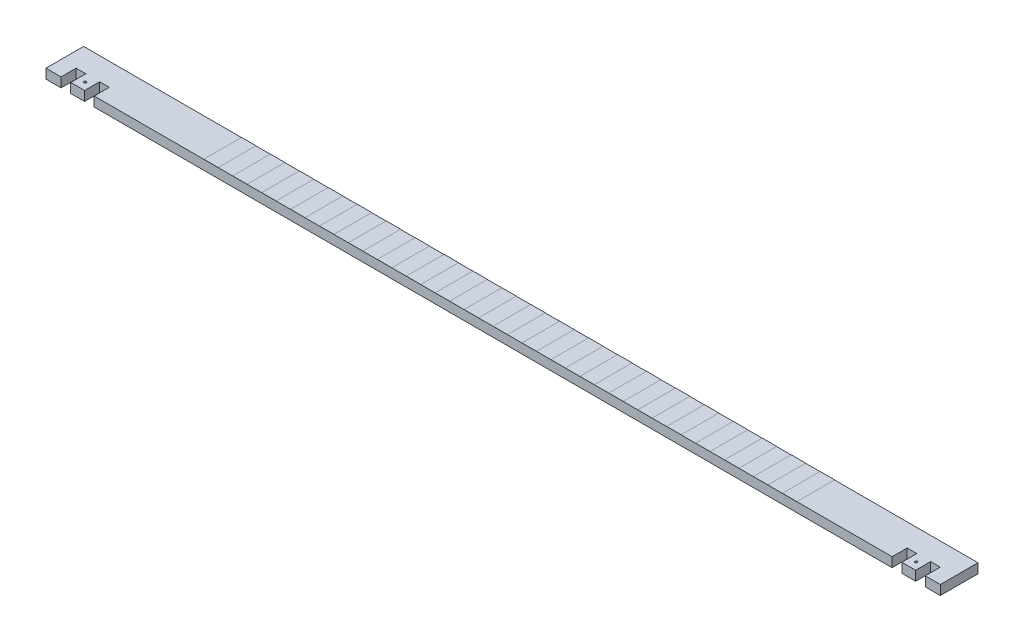
SolidWorks part; units mm, degrees
material "Acrylic (Medium-high impact)"
ref_plane "Front Plane" through (0, 0, 0) normal (0, 0, 1) x (1, 0, 0)
ref_plane "Top Plane" through (0, 0, 0) normal (0, 1, 0) x (1, 0, 0)
ref_plane "Right Plane" through (0, 0, 0) normal (1, 0, 0) x (0, 0, -1)
sketch "Sketch1" plane through (0, 0, 0) normal (0, 1, 0) x (1, 0, 0)
  line L0 (0, 12.5) -> (0, -12.5) construction
  line L1 (-296.75, 12.5) -> (296.75, 12.5)
  line L2 (-296.75, 12.5) -> (-296.75, -12.5)
  line L3 (-296.75, -12.5) -> (296.75, -12.5)
  line L4 (296.75, 12.5) -> (296.75, -12.5)
  line L5 (-264.75, -12.5) -> (-271.15, -12.5)
  line L6 (-264.75, -12.5) -> (-264.75, -2.5)
  line L7 (-264.75, -2.5) -> (-271.15, -2.5)
  line L8 (-271.15, -12.5) -> (-271.15, -2.5)
  line L9 (264.75, -12.5) -> (264.75, -2.5)
  line L10 (264.75, -2.5) -> (271.15, -2.5)
  line L11 (271.15, -12.5) -> (271.15, -2.5)
  line L12 (286.75, -12.5) -> (286.75, -2.5)
  line L13 (-286.75, -12.5) -> (-280.35, -12.5)
  line L14 (-286.75, -12.5) -> (-286.75, -2.5)
  line L15 (-286.75, -2.5) -> (-280.35, -2.5)
  line L16 (-280.35, -12.5) -> (-280.35, -2.5)
  line L17 (280.35, -12.5) -> (280.35, -2.5)
  line L18 (286.75, -2.5) -> (280.35, -2.5)
  line L19 (-280.35, -2.5) -> (-271.15, -2.5) construction
  circle A0 centre (-275.75, -7.5) radius 0.75
  circle A1 centre (275.75, -7.5) radius 0.75
  point P4 (0, -12.5)
  point P5 (296.75, 0)
  point P27 (-275.75, -2.5)
  dimension "D7" = 1.5
  dimension "D1" = 10
  dimension "D2" = 15
  dimension "D3" = 10
  dimension "D4" = 529.5
  dimension "D5" = 6.4
  dimension "D6" = 22
  dimension "D8" = 5
extrude "Boss-Extrude1" add sketch "Sketch1" along normal blind 6.35 contours L18 L12 L3 L4 L1 L2 L14 L15 L16 L8 L7 L6 L9 L10 L11 L17 A0 A1
ref_plane "Plane1" through (0, 6.45, 0) normal (0, 1, 0) x (1, 0, 0)
sketch "Sketch2" plane through (0, 6.45, 0) normal (0, 1, 0) x (1, 0, 0)
  line L0 (-264.75, -12.5) -> (264.75, -12.5) construction
  line L1 (-182.4, -12.5) -> (-192, -12.5)
  line L2 (-182.4, -12.5) -> (-182.4, 12.5)
  line L3 (-182.4, 12.5) -> (-192, 12.5)
  line L4 (-192, -12.5) -> (-192, 12.5)
  line L5 (-172.8, -12.5) -> (-172.8, 12.5)
  line L6 (-163.2, 12.5) -> (-172.8, 12.5)
  line L7 (-163.2, -12.5) -> (-163.2, 12.5)
  line L8 (-163.2, -12.5) -> (-172.8, -12.5)
  line L9 (-153.6, -12.5) -> (-153.6, 12.5)
  line L10 (-144, 12.5) -> (-153.6, 12.5)
  line L11 (-144, -12.5) -> (-144, 12.5)
  line L12 (-144, -12.5) -> (-153.6, -12.5)
  line L13 (-134.4, -12.5) -> (-134.4, 12.5)
  line L14 (-124.8, 12.5) -> (-134.4, 12.5)
  line L15 (-124.8, -12.5) -> (-124.8, 12.5)
  line L16 (-124.8, -12.5) -> (-134.4, -12.5)
  line L17 (-115.2, -12.5) -> (-115.2, 12.5)
  line L18 (-105.6, 12.5) -> (-115.2, 12.5)
  line L19 (-105.6, -12.5) -> (-105.6, 12.5)
  line L20 (-105.6, -12.5) -> (-115.2, -12.5)
  line L21 (-96, -12.5) -> (-96, 12.5)
  line L22 (-86.4, 12.5) -> (-96, 12.5)
  line L23 (-86.4, -12.5) -> (-86.4, 12.5)
  line L24 (-86.4, -12.5) -> (-96, -12.5)
  line L25 (-182.4, 0) -> (-172.8, 0) construction
  line L26 (-76.8, -12.5) -> (-76.8, 12.5)
  line L27 (-67.2, 12.5) -> (-76.8, 12.5)
  line L28 (-67.2, -12.5) -> (-67.2, 12.5)
  line L29 (-67.2, -12.5) -> (-76.8, -12.5)
  line L30 (-57.6, -12.5) -> (-57.6, 12.5)
  line L31 (-48, 12.5) -> (-57.6, 12.5)
  line L32 (-48, -12.5) -> (-48, 12.5)
  line L33 (-48, -12.5) -> (-57.6, -12.5)
  line L34 (-38.4, -12.5) -> (-38.4, 12.5)
  line L35 (-28.8, 12.5) -> (-38.4, 12.5)
  line L36 (-28.8, -12.5) -> (-28.8, 12.5)
  line L37 (-28.8, -12.5) -> (-38.4, -12.5)
  line L38 (-19.2, -12.5) -> (-19.2, 12.5)
  line L39 (-9.6, 12.5) -> (-19.2, 12.5)
  line L40 (-9.6, -12.5) -> (-9.6, 12.5)
  line L41 (-296.75, 12.5) -> (296.75, 12.5) construction
  line L42 (-9.6, -12.5) -> (-19.2, -12.5)
  line L43 (0, -12.5) -> (0, 12.5)
  line L44 (9.6, 12.5) -> (0, 12.5)
  line L45 (9.6, -12.5) -> (9.6, 12.5)
  line L46 (9.6, -12.5) -> (0, -12.5)
  line L47 (19.2, -12.5) -> (19.2, 12.5)
  line L48 (28.8, 12.5) -> (19.2, 12.5)
  line L49 (28.8, -12.5) -> (28.8, 12.5)
  line L50 (28.8, -12.5) -> (19.2, -12.5)
  line L51 (38.4, -12.5) -> (38.4, 12.5)
  line L52 (48, 12.5) -> (38.4, 12.5)
  line L53 (48, -12.5) -> (48, 12.5)
  line L54 (48, -12.5) -> (38.4, -12.5)
  line L55 (57.6, -12.5) -> (57.6, 12.5)
  line L56 (67.2, 12.5) -> (57.6, 12.5)
  line L57 (67.2, -12.5) -> (67.2, 12.5)
  line L58 (67.2, -12.5) -> (57.6, -12.5)
  line L59 (76.8, -12.5) -> (76.8, 12.5)
  line L60 (86.4, 12.5) -> (76.8, 12.5)
  line L61 (86.4, -12.5) -> (86.4, 12.5)
  line L62 (86.4, -12.5) -> (76.8, -12.5)
  line L63 (96, -12.5) -> (96, 12.5)
  line L64 (105.6, 12.5) -> (96, 12.5)
  line L65 (105.6, -12.5) -> (105.6, 12.5)
  line L66 (105.6, -12.5) -> (96, -12.5)
  line L67 (115.2, -12.5) -> (115.2, 12.5)
  line L68 (124.8, 12.5) -> (115.2, 12.5)
  line L69 (124.8, -12.5) -> (124.8, 12.5)
  line L70 (124.8, -12.5) -> (115.2, -12.5)
  line L71 (134.4, -12.5) -> (134.4, 12.5)
  line L72 (144, 12.5) -> (134.4, 12.5)
  line L73 (144, -12.5) -> (144, 12.5)
  line L74 (144, -12.5) -> (134.4, -12.5)
  line L75 (153.6, -12.5) -> (153.6, 12.5)
  line L76 (163.2, 12.5) -> (153.6, 12.5)
  line L77 (163.2, -12.5) -> (163.2, 12.5)
  line L78 (163.2, -12.5) -> (153.6, -12.5)
  line L79 (172.8, -12.5) -> (172.8, 12.5)
  line L80 (182.4, 12.5) -> (172.8, 12.5)
  line L81 (182.4, -12.5) -> (182.4, 12.5)
  line L82 (182.4, -12.5) -> (172.8, -12.5)
  line L83 (192, -12.5) -> (192, 12.5)
  line L84 (201.6, 12.5) -> (192, 12.5)
  line L85 (201.6, -12.5) -> (201.6, 12.5)
  line L86 (201.6, -12.5) -> (192, -12.5)
  dimension "D2" = 9.6
  dimension "D1" = 21
surface "Surface-Plane1" sketch "Sketch2"
equation "\"Acrylic\"= 0.25in"
equation "\"Wood\"= 0.125in"
equation "\"ScrewHole\"= 0.15625in"
equation "\"AcryTab\"= 0.5in"
equation "\"WoodTab\"= 0.25in"
equation "\"SlideLength\"= 11in"
equation "\"SidePegs\"= 4.625in"
equation "\"NutHole_L\"= 0.21875in"
equation "\"NutHole_W\"= 0.09375in"
equation "\"D1@Boss-Extrude1\" = \"Acrylic\""
